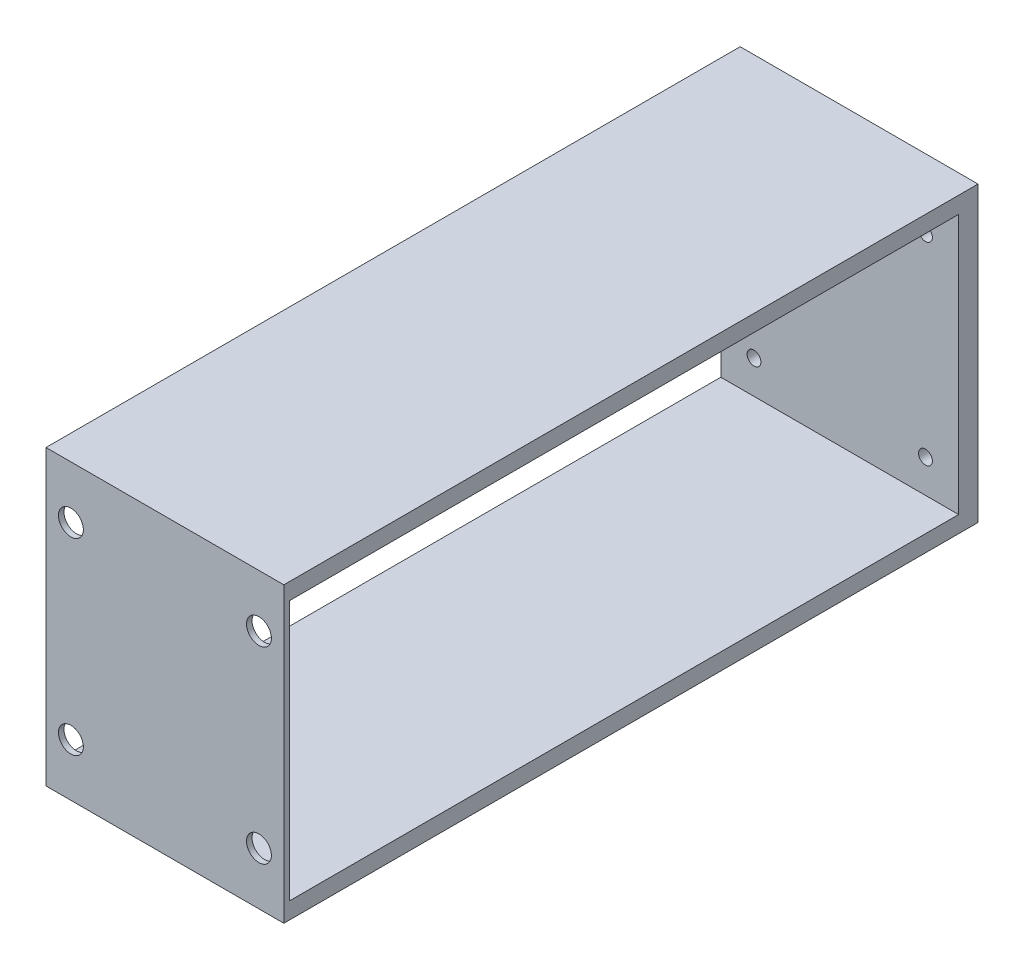
SolidWorks part; units mm, degrees
ref_plane "前视基准面" through (0, 0, 0) normal (0, 0, 1) x (1, 0, 0)
ref_plane "上视基准面" through (0, 0, 0) normal (0, 1, 0) x (1, 0, 0)
ref_plane "右视基准面" through (0, 0, 0) normal (1, 0, 0) x (0, 0, -1)
sketch "草图1" plane through (0, 0, 0) normal (0, 0, 1) x (1, 0, 0)
  line L1 (-21.5, -23.5) -> (21.5, -23.5)
  line L2 (-21.5, -23.5) -> (-21.5, 23.5)
  line L3 (-21.5, 23.5) -> (21.5, 23.5)
  line L4 (21.5, -23.5) -> (21.5, 23.5)
  line L5 (-21.5, -23.5) -> (21.5, 23.5) construction
  line L6 (-21.5, 23.5) -> (21.5, -23.5) construction
  point P0 (0, 0)
  dimension "D1" = 43
  dimension "D2" = 47
extrude "凸台-拉伸1" add sketch "草图1" along normal blind 1
sketch "草图2" plane through (0, 23.5, 0) normal (0, 1, 0) x (1, 0, 0)
  line L0 (21.5, -1) -> (21.5, 0) construction
  line L1 (-21.5, -1) -> (21.5, -1)
  line L2 (-21.5, -1) -> (-21.5, 121)
  line L3 (-21.5, 121) -> (21.5, 121)
  line L4 (21.5, -1) -> (21.5, 121)
  dimension "D1" = 122
extrude "凸台-拉伸2" add sketch "草图2" along normal blind 3
sketch "草图3" plane through (0, -23.5, 0) normal (0, -1, 0) x (1, 0, 0)
  line L0 (-21.5, -121) -> (-21.5, 0) construction
  line L1 (21.5, 1) -> (-21.5, 1)
  line L2 (21.5, 1) -> (21.5, -121)
  line L3 (21.5, -121) -> (-21.5, -121)
  line L4 (-21.5, 1) -> (-21.5, -121)
  line L5 (21.5, -121) -> (-21.5, -121) construction
extrude "凸台-拉伸3" add sketch "草图3" along normal blind 3
sketch "草图5" plane through (0, 0, 1) normal (0, 0, 1) x (1, 0, 0)
  line L0 (-21.5, 26.5) -> (-21.5, -26.5) construction
  line L2 (21.5, -26.5) -> (-21.5, -26.5) construction
  circle A0 centre (-17, -17) radius 2.25
  dimension "D1" = 4.5
  dimension "D2" = 4.5
  dimension "D3" = 9.5
extrude "切除-拉伸1" cut sketch "草图5" against normal blind 10 contours A0
pattern_linear "阵列(线性)1" count 2 spacing 34 along (0, 1, 0) count 2 spacing 34 along (1, 0, 0) of "切除-拉伸1"
sketch "草图6" plane through (0, 0, -121) normal (0, 0, -1) x (-1, 0, 0)
  line L1 (-21.5, 26.5) -> (21.5, 26.5)
  line L2 (-21.5, 26.5) -> (-21.5, -26.5)
  line L3 (-21.5, -26.5) -> (21.5, -26.5)
  line L4 (21.5, 26.5) -> (21.5, -26.5)
extrude "凸台-拉伸4" add sketch "草图6" along normal blind 3.5
hole_wizard "M3 螺纹孔1" positions "3D草图1" profile "草图7" tap size "M3" standard "GB"
sketch3d "3D草图1"
  line L0 (-21.5, -23.5, -121) -> (-21.5, 23.5, -121) construction
  line L3 (-21.5, -23.5, -121) -> (21.5, -23.5, -121) construction
  line L4 (21.5, 23.5, -121) -> (21.5, -23.5, -121) construction
  line L5 (21.5, 23.5, -121) -> (-21.5, 23.5, -121) construction
  point P0 (-15.5, 17.5, -121)
  point P2 (15.5, 17.5, -121)
  point P4 (-15.5, -17.5, -121)
  point P6 (15.5, -17.5, -121)
  dimension "D1" = 6
  dimension "D2" = 6
  dimension "D3" = 6
  dimension "D4" = 6
  dimension "D5" = 6
  dimension "D6" = 6
  dimension "D7" = 6
  dimension "D8" = 6
sketch "草图7" plane through (-15.5, 17.5, -121) normal (1, 0, 0) x (0, -1, 0)
  line L0 (0, 0) -> (0, 8.2511)
  line L1 (0, 8.2511) -> (1.25, 7.5)
  line L2 (1.25, 7.5) -> (1.25, 0)
  line L5 (1.25, 0) -> (0, 0)
  line L10 (0, 8.2511) -> (-1.25, 7.5) construction
  line L11 (0, -6.35) -> (0, 107.95) construction
  dimension "螺纹孔钻头直径" = 2.5
  dimension "螺纹孔钻头深度" = 7.5
  dimension "导头角度" = 118
cosmetic thread "孔螺蚊线1" parameters "D1"=3.5, "D2"=3
cosmetic thread "孔螺蚊线2" parameters "D1"=3.5, "D2"=3
cosmetic thread "孔螺蚊线3" parameters "D1"=3.5, "D2"=3
cosmetic thread "孔螺蚊线4" parameters "D1"=3.5, "D2"=3
